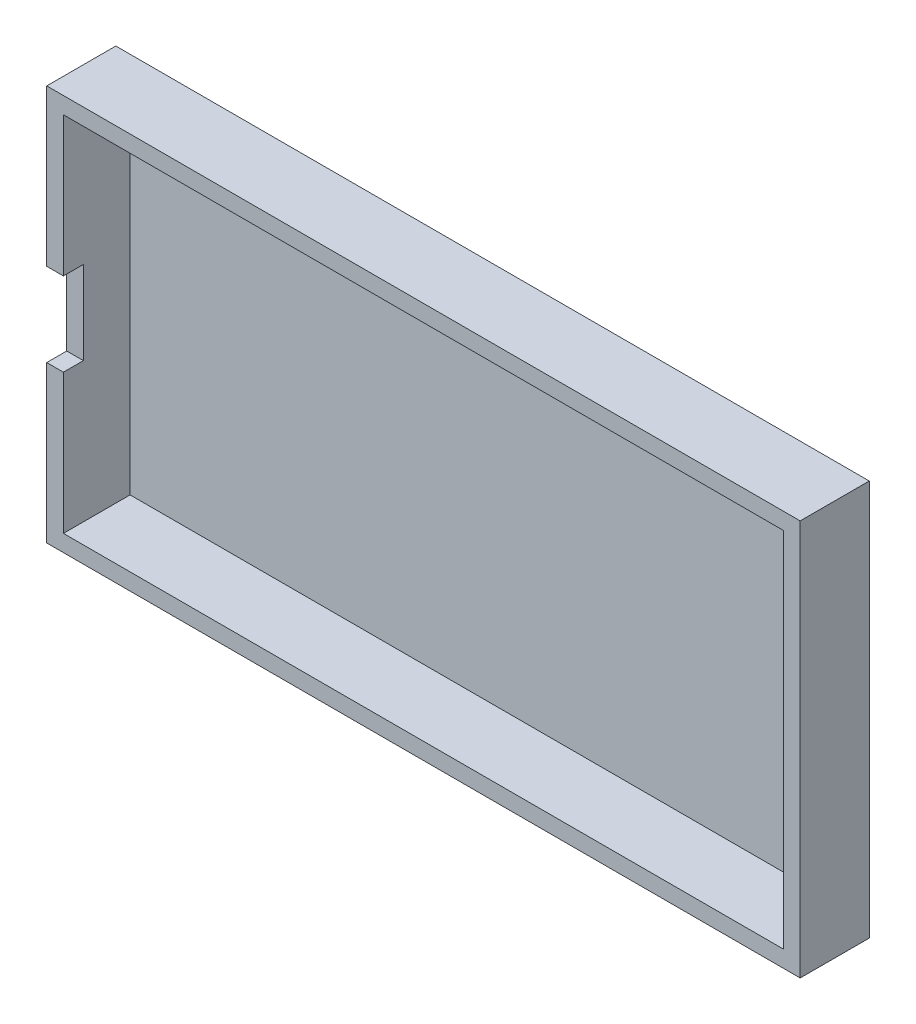
SolidWorks part; units mm, degrees
ref_plane "Front Plane" through (0, 0, 0) normal (0, 0, 1) x (1, 0, 0)
ref_plane "Top Plane" through (0, 0, 0) normal (0, 1, 0) x (1, 0, 0)
ref_plane "Right Plane" through (0, 0, 0) normal (1, 0, 0) x (0, 0, -1)
sketch3d "3DSketch1"
  line L0 (-0.0576, -0.0297, 0.0584) -> (-0.0548, -0.0269, 0.0613)
  line L1 (-0.0548, -0.0269, 0.0613) -> (0.0526, -0.0269, 0.0613)
  line L2 (0.0526, -0.0269, 0.0613) -> (0.0554, -0.0297, 0.0584)
  line L3 (0.0554, -0.0297, 0.0584) -> (-0.0576, -0.0297, 0.0584)
  line L4 (-0.0576, -0.0297, 0.0444) -> (-0.0548, -0.0269, 0.0416)
  line L5 (-0.0548, -0.0269, 0.0416) -> (0.0526, -0.0269, 0.0416)
  line L6 (0.0526, -0.0269, 0.0416) -> (0.0554, -0.0297, 0.0444)
  line L7 (0.0554, -0.0297, 0.0444) -> (-0.0576, -0.0297, 0.0444)
  line L8 (0.0554, -0.0297, 0.0444) -> (0.0554, -0.0297, 0.0584)
  line L9 (-0.0576, -0.0297, 0.0584) -> (-0.0576, -0.0297, 0.0444)
  line L10 (-0.0548, -0.0269, 0.0613) -> (-0.0548, 0.0269, 0.0613)
  line L11 (-0.0548, 0.0269, 0.0613) -> (-0.0576, 0.0297, 0.0584)
  line L12 (-0.0576, 0.0297, 0.0584) -> (-0.0576, -0.0297, 0.0584)
  line L13 (-0.0576, 0.0297, 0.0584) -> (-0.0576, 0.0297, 0.0444)
  line L14 (-0.0576, 0.0297, 0.0444) -> (-0.0576, -0.0297, 0.0444)
  line L15 (-0.0548, -0.0269, 0.0416) -> (-0.0548, 0.0269, 0.0416)
  line L16 (-0.0548, 0.0269, 0.0416) -> (-0.0576, 0.0297, 0.0444)
  line L17 (-0.0548, 0.0269, 0.0613) -> (0.0526, 0.0269, 0.0613)
  line L18 (0.0526, 0.0269, 0.0613) -> (0.0526, -0.0269, 0.0613)
  line L19 (0.0554, -0.0297, 0.0584) -> (0.0554, 0.0297, 0.0584)
  line L20 (0.0554, 0.0297, 0.0584) -> (0.0526, 0.0269, 0.0613)
ref_plane "Plane1" through (0, 0, 0.0416) normal (0, 0, 1) x (1, 0, 0)
ref_plane "Plane2" through (0, -0.0297, 0) normal (0, 1, 0) x (1, 0, 0)
sketch "Sketch6" plane through (0, -0.0297, 0) normal (0, 1, 0) x (1, 0, 0)
  line L0 (-0.0576, -0.0444) -> (-0.0548, -0.0416)
  line L2 (-0.0576, -0.0444) -> (-0.0576, -0.0584)
  line L4 (0.0554, -0.0444) -> (0.0554, -0.0584)
  line L5 (-0.0548, -0.0416) -> (0.0526, -0.0416)
  line L6 (0.0526, -0.0416) -> (0.0554, -0.0444)
  line L7 (-0.0576, -0.0584) -> (-0.0548, -0.0613)
  line L8 (-0.0548, -0.0613) -> (0.0526, -0.0613)
  line L9 (0.0526, -0.0613) -> (0.0554, -0.0584)
extrude "Boss-Extrude2" add sketch "Sketch6" along normal up to vertex (0.0594 mm away)
ref_plane "Plane3" through (-0.0576, 0, 0) normal (1, 0, 0) x (0, 0, -1)
sketch "Sketch10" plane through (-0.0576, 0, 0) normal (1, 0, 0) x (0, 0, -1)
  line L0 (-0.0613, 0.0269) -> (-0.0584, 0.0297)
  line L1 (-0.0416, 0.0269) -> (-0.0444, 0.0297)
  line L5 (-0.0584, -0.0297) -> (-0.0613, -0.0269)
  line L6 (-0.0444, -0.0297) -> (-0.0416, -0.0269)
  line L8 (-0.0613, -0.0269) -> (-0.0613, -0.0297)
  line L9 (-0.0613, 0.0297) -> (-0.0584, 0.0297)
  line L10 (-0.0613, 0.0297) -> (-0.0613, 0.0269)
  line L11 (-0.0613, -0.0297) -> (-0.0584, -0.0297)
  line L12 (-0.0416, 0.0297) -> (-0.0416, 0.0269)
  line L13 (-0.0416, -0.0269) -> (-0.0416, -0.0297)
  line L14 (-0.0444, 0.0297) -> (-0.0416, 0.0297)
  line L15 (-0.0444, -0.0297) -> (-0.0416, -0.0297)
extrude "Cut-Extrude2" cut sketch "Sketch10" along normal through all
sketch "Sketch11" plane through (-0.0576, 0, 0) normal (-1, 0, 0) x (0, 0, 1)
  line L0 (0.0548, 0.0297) -> (0.0548, -0.0297)
  line L1 (0.0444, 0.0297) -> (0.0584, 0.0297) construction
  line L2 (0.0444, -0.0297) -> (0.0584, -0.0297) construction
  line L3 (0.0548, -0.0297) -> (0.0584, -0.0297)
  line L4 (0.0584, -0.0297) -> (0.0613, -0.0269)
  line L5 (0.0613, -0.0269) -> (0.0613, 0.0269)
  line L6 (0.0613, 0.0269) -> (0.0584, 0.0297)
  line L7 (0.0584, 0.0297) -> (0.0548, 0.0297)
  line L8 (0.0416, 0.0269) -> (0.0416, -0.0269) construction
  dimension "D1" = 0.0132
extrude "Cut-Extrude3" cut sketch "Sketch11" against normal through all
sketch "Sketch12" plane through (0, 0, 0.0548) normal (0, 0, 1) x (1, 0, 0)
  line L0 (-0.0576, 0.0297) -> (-0.0576, -0.0297) construction
  line L1 (-0.0551, 0.0272) -> (0.0529, 0.0272)
  line L2 (-0.0551, 0.0272) -> (-0.0551, -0.0272)
  line L3 (-0.0551, -0.0272) -> (0.0529, -0.0272)
  line L4 (0.0529, 0.0272) -> (0.0529, -0.0272)
  line L5 (0.0554, 0.0297) -> (-0.0576, 0.0297) construction
  line L6 (0.0554, 0.0297) -> (0.0554, -0.0297) construction
  line L7 (0.0554, -0.0297) -> (-0.0576, -0.0297) construction
  dimension "D1" = 0.0025
  dimension "D2" = 0.0025
  dimension "D3" = 0.0025
  dimension "D4" = 0.0025
extrude "Cut-Extrude4" cut sketch "Sketch12" against normal blind 0.01
sketch "Sketch13" plane through (-0.0576, 0, 0) normal (-1, 0, 0) x (0, 0, 1)
  line L0 (0.0548, 0.0297) -> (0.0548, -0.0297) construction
  line L1 (0.0548, 0.0063) -> (0.0518, 0.0063)
  line L2 (0.0548, 0.0063) -> (0.0548, -0.0062)
  line L3 (0.0548, -0.0062) -> (0.0518, -0.0062)
  line L4 (0.0518, 0.0063) -> (0.0518, -0.0062)
  line L6 (0.0548, 0.0297) -> (0.0548, -0.0297) construction
  point P10 (0.0548, 0)
  point P11 (0.0548, 0)
  dimension "D1" = 0.0125
  dimension "D2" = 0.003
extrude "Cut-Extrude5" cut sketch "Sketch13" against normal blind 0.01
